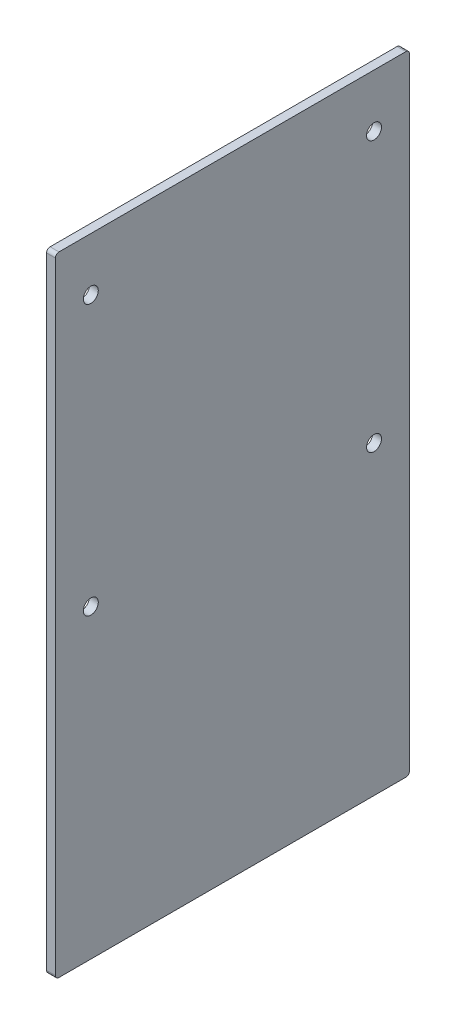
SolidWorks part; units mm, degrees
material "PE High Density"
ref_plane "Front Plane" through (0, 0, 0) normal (0, 0, 1) x (1, 0, 0)
ref_plane "Top Plane" through (0, 0, 0) normal (0, 1, 0) x (1, 0, 0)
ref_plane "Right Plane" through (0, 0, 0) normal (1, 0, 0) x (0, 0, -1)
sketch "Sketch1" plane through (0, 0, 0) normal (1, 0, 0) x (0, 0, -1)
  line L1 (0, 0) -> (254, 0)
  line L2 (0, 0) -> (0, 438.15)
  line L3 (0, 438.15) -> (254, 438.15)
  line L4 (254, 0) -> (254, 438.15)
  dimension "D1" = 254
  dimension "D2" = 438.15
extrude "Boss-Extrude1" add sketch "Sketch1" along normal blind 6.35
hole_wizard "27/64 (0.42188) Diameter Hole1" positions "Sketch2" profile "Sketch3" hole size "27/64" standard "ANSI Inch" end condition through all
sketch "Sketch2" plane through (6.35, 0, 0) normal (1, 0, 0) x (0, 0, -1)
  line L0 (127, 438.15) -> (127, 0) construction
  line L1 (254, 438.15) -> (0, 438.15) construction
  line L2 (0, 0) -> (254, 0) construction
  line L3 (254, 219.075) -> (0, 219.075) construction
  line L4 (254, 0) -> (254, 438.15) construction
  line L5 (0, 438.15) -> (0, 0) construction
  point P0 (25.4, 412.75)
  point P2 (25.4, 219.075)
  point P28 (228.6, 219.075)
  point P29 (228.6, 412.75)
  dimension "D1" = 25.4
  dimension "D2" = 25.4
sketch "Sketch3" plane through (6.35, 412.75, -25.4) normal (0, 1, 0) x (0, 0, -1)
  line L0 (0, 0) -> (0, 6.35)
  line L1 (0, 6.35) -> (5.3579, 6.35)
  line L2 (5.3579, 6.35) -> (5.3579, 0)
  line L5 (5.3579, 0) -> (0, 0)
  line L11 (0, -6.35) -> (0, 107.95) construction
  dimension "Thru Hole Dia." = 10.7158
  dimension "Thru Hole Depth" = 6.35
sketch "Sketch4" plane through (6.35, 0, 0) normal (1, 0, 0) x (0, 0, -1)
  line L0 (254, 0) -> (254, 438.15) construction
  line L1 (0, 438.15) -> (254, 438.15)
  line L2 (0, 438.15) -> (0, 450.85)
  line L3 (0, 450.85) -> (254, 450.85)
  line L4 (254, 438.15) -> (254, 450.85)
  dimension "D1" = 12.7
extrude "Boss-Extrude2" add sketch "Sketch4" against normal up to surface (6.35 mm away) up to face at (0, 412.75, -30.7579)
fillet "Fillet1" radius 2.54 4 edges at (3.175, 0, -254) (3.175, 0, 0) (3.175, 450.85, 0) (3.175, 450.85, -254)
